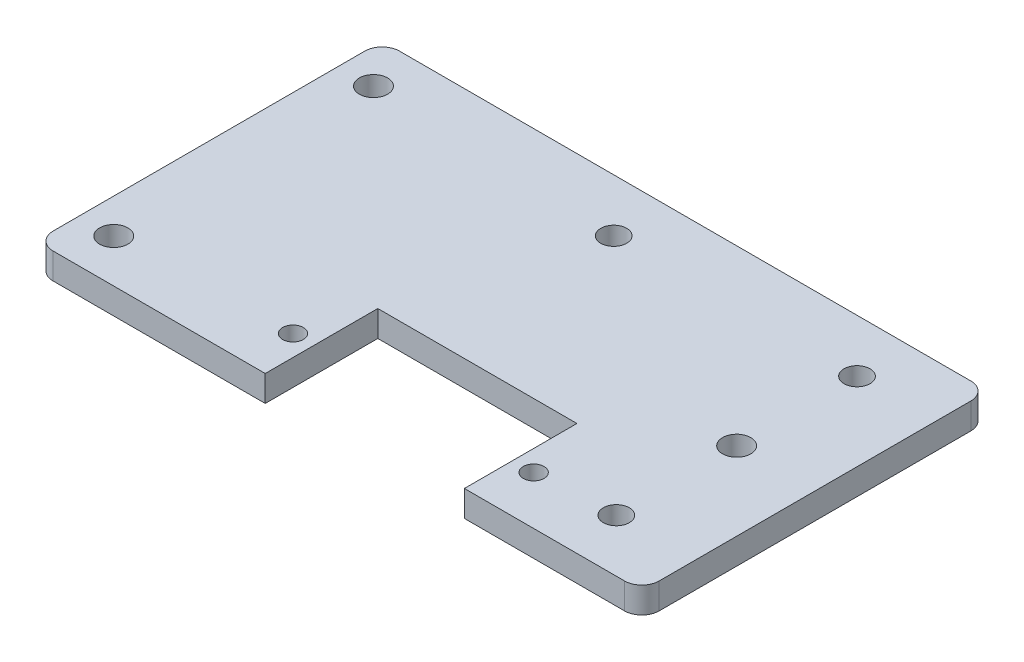
SolidWorks part; units mm, degrees
material "Acrylic (Medium-high impact)"
ref_plane "Front Plane" through (0, 0, 0) normal (0, 0, 1) x (1, 0, 0)
ref_plane "Top Plane" through (0, 0, 0) normal (0, 1, 0) x (1, 0, 0)
ref_plane "Right Plane" through (0, 0, 0) normal (1, 0, 0) x (0, 0, -1)
sketch "Sketch1" plane through (0, 0, 0) normal (0, 1, 0) x (1, 0, 0)
  line L1 (-35, 20) -> (35, 20)
  line L2 (-35, 20) -> (-35, -20)
  line L3 (-35, -20) -> (35, -20)
  line L4 (35, 20) -> (35, -20)
  line L5 (-35, 20) -> (35, -20) construction
  line L6 (-35, -20) -> (35, 20) construction
  point P0 (0, 0)
  dimension "D1" = 70
  dimension "D2" = 40
extrude "Boss-Extrude1" add sketch "Sketch1" along normal blind 3
hole_wizard "Ø3.0mm Dowel Hole1" positions "Sketch2" profile "Sketch3" hole size "Ø3.0" standard "ANSI Metric" end condition through all
sketch "Sketch2" plane through (0, 3, 0) normal (0, 1, 0) x (1, 0, 0)
  line L2 (35, -20) -> (35, 20) construction
  line L3 (-35, -20) -> (35, -20) construction
  point P0 (-2.15, 13.9)
  point P2 (25.95, 13.9)
  point P6 (25.95, -13.9)
  dimension "D3" = 27.8
  dimension "D1" = 37.15
  dimension "D2" = 9.05
  dimension "D4" = 6.1
sketch "Sketch3" plane through (-2.15, 3, -13.9) normal (1, 0, 0) x (0, 0, 1)
  line L0 (0, 0) -> (0, 3)
  line L1 (0, 3) -> (1.5, 3)
  line L2 (1.5, 3) -> (1.5, 0)
  line L5 (1.5, 0) -> (0, 0)
  line L11 (0, -6.35) -> (0, 107.95) construction
  dimension "Thru Hole Dia." = 3
  dimension "Thru Hole Depth" = 3
hole_wizard "#4 Clearance Hole1" positions "Sketch4" profile "Sketch5" hole size "#4" standard "ANSI Inch" end condition through all
sketch "Sketch4" plane through (0, 3, 0) normal (0, 1, 0) x (1, 0, 0)
  line L0 (-35, 20) -> (-35, -20) construction
  line L1 (-35, -20) -> (35, -20) construction
  line L2 (35, 20) -> (-35, 20) construction
  line L4 (35, -20) -> (35, 20) construction
  point P0 (-31, 15)
  point P2 (-31, -15)
  point P11 (25.95, 0)
  dimension "D1" = 4
  dimension "D2" = 4
  dimension "D3" = 5
  dimension "D4" = 5
  dimension "D5" = 9.05
sketch "Sketch5" plane through (-31, 3, -15) normal (1, 0, 0) x (0, 0, 1)
  line L0 (0, 0) -> (0, 3)
  line L1 (0, 3) -> (1.6319, 3)
  line L2 (1.6319, 3) -> (1.6319, 0)
  line L5 (1.6319, 0) -> (0, 0)
  line L11 (0, -6.35) -> (0, 107.95) construction
  dimension "Thru Hole Dia." = 3.2639
  dimension "Thru Hole Depth" = 3
hole_wizard "M2 Clearance Hole1" positions "Sketch6" profile "Sketch7" hole size "M2" standard "ANSI Metric" end condition through all
sketch "Sketch6" plane through (0, 3, 0) normal (0, 1, 0) x (1, 0, 0)
  line L0 (-35, -20) -> (35, -20) construction
  line L1 (35, -20) -> (35, 20) construction
  point P0 (-10.9, -14.4)
  point P2 (16.9, -14.4)
  dimension "D1" = 27.8
  dimension "D2" = 5.6
  dimension "D3" = 18.1
sketch "Sketch7" plane through (-10.9, 3, 14.4) normal (1, 0, 0) x (0, 0, 1)
  line L0 (0, 0) -> (0, 3)
  line L1 (0, 3) -> (1.2, 3)
  line L2 (1.2, 3) -> (1.2, 0)
  line L5 (1.2, 0) -> (0, 0)
  line L11 (0, -6.35) -> (0, 107.95) construction
  dimension "Thru Hole Dia." = 2.4
  dimension "Thru Hole Depth" = 3
sketch "Sketch8" plane through (0, 3, 0) normal (0, 1, 0) x (1, 0, 0)
  line L0 (-35, -20) -> (35, -20) construction
  line L1 (-8.5, -20) -> (14.5, -20)
  line L2 (-8.5, -20) -> (-8.5, -7)
  line L3 (-8.5, -7) -> (14.5, -7)
  line L4 (14.5, -20) -> (14.5, -7)
  circle A0 centre (16.9, -14.4) radius 1.2 construction
  point P6 (3, -7)
  dimension "D1" = 13
  dimension "D2" = 23
  dimension "D3" = 13.9
extrude "Cut-Extrude1" cut sketch "Sketch8" against normal blind 10
fillet "Fillet1" radius 2 4 edges at (35, 1.5, -20) (35, 1.5, 20) (-35, 1.5, 20) (-35, 1.5, -20)
equation "\"D4@Sketch2\"=(40-\"D3@Sketch2\")/2"
equation "\"D4@Sketch4\"=\"D3@Sketch4\""
equation "\"D2@Sketch4\"=\"D1@Sketch4\""
equation "\"D3@Sketch6\"=9.05*2"
